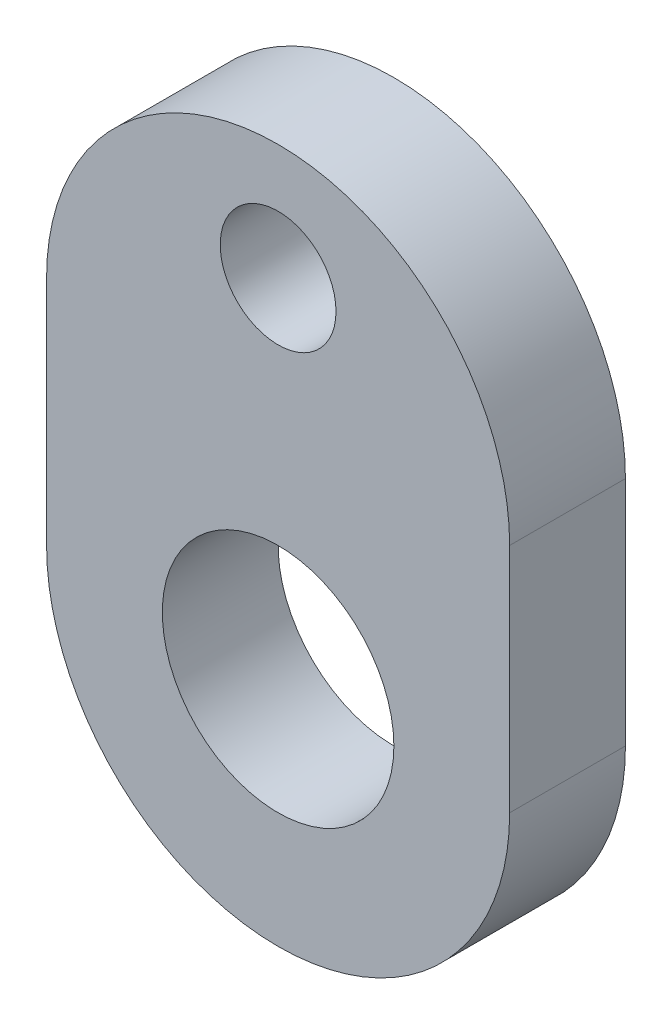
SolidWorks part; units mm, degrees
ref_plane "Front Plane" through (0, 0, 0) normal (0, 0, 1) x (1, 0, 0)
ref_plane "Top Plane" through (0, 0, 0) normal (0, 1, 0) x (1, 0, 0)
ref_plane "Right Plane" through (0, 0, 0) normal (1, 0, 0) x (0, 0, -1)
sketch "Sketch2" plane through (0, 0, 0) normal (0, 0, 1) x (1, 0, 0)
  line L0 (0, 0) -> (0, 19.05) construction
  line L1 (0, 19.05) -> (0, 6.35) construction
  line L2 (-12.7, 0) -> (-12.7, 12.7)
  line L3 (12.7, 0) -> (12.7, 12.7)
  circle A0 centre (0, 0) radius 6.35
  circle A1 centre (0, 19.05) radius 3.175
  arc A2 (-12.7, 0) -> (12.7, 0) centre (0, 0) ccw
  arc A3 (-12.7, 12.7) -> (12.7, 12.7) centre (0, 12.7) cw
  circle A5 centre (0, 0) radius 12.7 construction
  point P11 (12.1451, 3.7131)
  dimension "D1" = 12.7
  dimension "D3" = 6.35
  dimension "D5" = 12.7
  dimension "D2" = 12.7
  dimension "D4" = 12.7
extrude "Boss-Extrude1" add sketch "Sketch2" along normal blind 6.35
